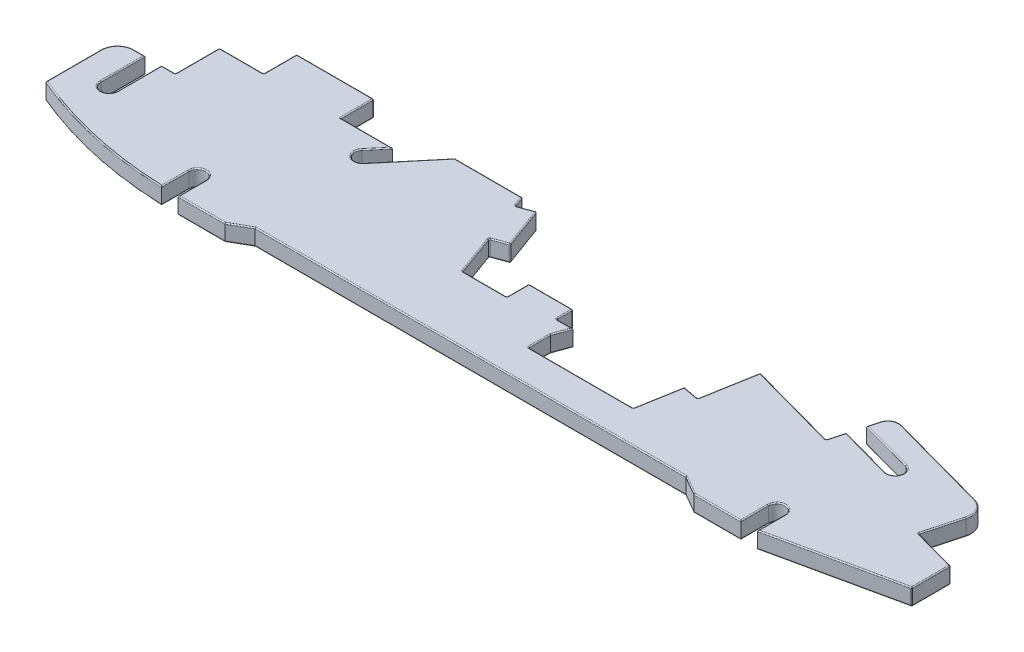
SolidWorks part; units mm, degrees
ref_plane "Front Plane" through (0, 0, 0) normal (0, 0, 1) x (1, 0, 0)
ref_plane "Top Plane" through (0, 0, 0) normal (0, 1, 0) x (1, 0, 0)
ref_plane "Right Plane" through (0, 0, 0) normal (1, 0, 0) x (0, 0, -1)
sketch "Sketch1" plane through (0, 0, 0) normal (0, 1, 0) x (1, 0, 0)
  line L0 (-1.5, 0) -> (-1.5, -5)
  line L1 (1.5, 0) -> (1.5, -5)
  line L2 (-103.5, -5) -> (-95, -5)
  line L3 (24.5, 0) -> (24.5, 7)
  line L4 (-103.5, -5) -> (-103.5, 0)
  line L5 (-106.5, 0) -> (-106.5, -5)
  line L6 (-128.5, 6) -> (-128.5, 14)
  line L7 (-125.5, 6) -> (-125.5, 14)
  line L8 (-133.5, 11) -> (-133.5, 1)
  line L9 (1.5, -5) -> (24.5, 0)
  line L10 (-91.5359, -3) -> (-13.4641, -3)
  line L11 (-95, -5) -> (-91.5359, -3)
  line L12 (-10, -5) -> (-13.4641, -3)
  line L13 (-10, -5) -> (-1.5, -5)
  line L14 (-105, 0) -> (0, 0) construction
  line L15 (-52.5, 0) -> (-52.5, -7.0386) construction
  line L16 (-48, 3) -> (-29, 3)
  line L18 (-48, 3) -> (-48, 7)
  line L19 (-48, 7) -> (-46.9081, 10)
  line L20 (-46.9081, 10) -> (-49.9081, 10)
  line L21 (-49.9081, 10) -> (-49.9081, 13)
  line L22 (-49.9081, 13) -> (-57.9081, 13)
  line L23 (-57.9081, 13) -> (-57.9081, 9)
  line L24 (-57.9081, 9) -> (-65.9081, 9)
  line L25 (-65.9081, 9) -> (-68.6443, 16.5175)
  line L26 (-84.3291, 26) -> (-72.0956, 26)
  line L27 (-68.6443, 16.5175) -> (-65.8252, 17.5436)
  line L28 (-65.8252, 17.5436) -> (-68.5613, 25.0611)
  line L29 (-68.5613, 25.0611) -> (-71.3804, 24.0351)
  line L30 (-71.3804, 24.0351) -> (-72.0956, 26)
  line L31 (-115, 28) -> (-101, 28)
  line L32 (-101, 28) -> (-101, 22)
  line L33 (-101, 22) -> (-91.6017, 22)
  line L34 (-91.6017, 22) -> (-94.1491, 18.9642)
  line L35 (-91.8509, 17.0358) -> (-84.3291, 26)
  line L36 (-115, 28) -> (-115, 22)
  line L37 (-115, 22) -> (-123, 22)
  line L38 (-123, 22) -> (-123, 14)
  line L39 (-123, 14) -> (-125.5, 14)
  line L41 (-29, 3) -> (-27.6108, 10.8785)
  line L42 (-27.6108, 10.8785) -> (-24.6564, 10.3575)
  line L43 (-24.6564, 10.3575) -> (-22.9562, 20)
  line L44 (24.5, 7) -> (16.587, 9.1677)
  line L45 (-6.5602, 15.5085) -> (-5.7676, 18.4019)
  line L46 (-5.7676, 18.4019) -> (3.8771, 15.7599)
  line L47 (4.6697, 18.6533) -> (-4.975, 21.2953)
  line L48 (-4.975, 21.2953) -> (-4.4466, 23.2243)
  line L49 (-1.9893, 24.6248) -> (16.3356, 19.6049)
  line L50 (18.4364, 15.9189) -> (16.587, 9.1677)
  line L51 (-6.5602, 15.5085) -> (-22.9562, 20)
  line L52 (-128.5, 14) -> (-130.5, 14)
  arc A0 (1.5, 0) -> (-1.5, 0) centre (0, 0) ccw
  arc A1 (-103.5, 0) -> (-106.5, 0) centre (-105, 0) ccw
  arc A2 (-128.5, 6) -> (-125.5, 6) centre (-127, 6) ccw
  arc A3 (-133.5, 11) -> (-130.5, 14) centre (-130.5, 11) cw
  arc A4 (-133.5, 1) -> (-106.5, -5) centre (-104.0092, 69.9586) ccw
  arc A5 (-94.1491, 18.9642) -> (-91.8509, 17.0358) centre (-93, 18) ccw
  arc A6 (3.8771, 15.7599) -> (4.6697, 18.6533) centre (4.2734, 17.2066) ccw
  arc A7 (16.3356, 19.6049) -> (18.4364, 15.9189) centre (15.543, 16.7115) cw
  arc A8 (-4.4466, 23.2243) -> (-1.9893, 24.6248) centre (-2.5177, 22.6959) cw
  point P68 (19.229, 18.8123)
  point P71 (-3.9182, 25.1532)
  dimension "D1" = 3
  dimension "D3" = 3
  dimension "D10" = 75
  dimension "D36" = 14
  dimension "D42" = 1.5
  dimension "D49" = 23
  dimension "D52" = 1.5
  dimension "D56" = 3
  dimension "D57" = 2
  dimension "D8" = 3
  dimension "D47" = 3
  dimension "D2" = 24.5
  dimension "D4" = 105
  dimension "D6" = 28.5
  dimension "D7" = 10.5
  dimension "D9" = 6
  dimension "D11" = 5
  dimension "D12" = 5
  dimension "D13" = 12
  dimension "D14" = 2
  dimension "D15" = 30
  dimension "D16" = 30
  dimension "D17" = 85
  dimension "D18" = 42.5
  dimension "D19" = 6
  dimension "D20" = 4
  dimension "D21" = 48
  dimension "D22" = 80
  dimension "D23" = 20
  dimension "D24" = 13
  dimension "D25" = 8
  dimension "D26" = 8
  dimension "D27" = 12
  dimension "D28" = 3
  dimension "D29" = 3
  dimension "D30" = 29
  dimension "D31" = 70
  dimension "D32" = 8
  dimension "D33" = 8
  dimension "D34" = 3
  dimension "D35" = 33
  dimension "D37" = 6
  dimension "D38" = 8
  dimension "D39" = 6.5
  dimension "D40" = 8
  dimension "D41" = 12
  dimension "D43" = 40
  dimension "D44" = 23
  dimension "D45" = 3
  dimension "D46" = 8
  dimension "D48" = 29
  dimension "D50" = 17
  dimension "D51" = 3
  dimension "D53" = 10
  dimension "D54" = 4
  dimension "D55" = 24
  dimension "D58" = 8
extrude "Boss-Extrude1" add sketch "Sketch1" along normal blind 3
fillet "Fillet1" radius 0.2 117 edges at (24.5, 1.5, -7) (-49.9081, 1.5, -13) (-57.9081, 1.5, -13) (-68.5613, 1.5, -25.0611) (1.5, 0, 2.5) (24.5, 0, -3.5) (20.5435, 0, -8.0838) (18.1494, 0, -18.197) (7.1732, 0, -22.1149) (-3.508, 0, -24.4335) (-4.7108, 0, -22.2598) (-0.1527, 0, -19.9743) (5.7201, 0, -16.8103) (-0.9453, 0, -17.0809) (-6.1639, 0, -16.9552) (-14.7582, 0, -17.7543) (-23.8063, 0, -15.1788) (-26.1336, 0, -10.618) (-28.3054, 0, -6.9392) (-38.5, 0, -3) (-47.454, 0, -8.5) (-48.4081, 0, -10) (-49.9081, 0, -11.5) (-53.9081, 0, -13) (-57.9081, 0, -11) (-61.9081, 0, -9) (-67.2762, 0, -12.7588) (-67.2347, 0, -17.0306) (-69.9709, 0, -24.5481) (-78.2123, 0, -26) (-88.09, 0, -21.5179) (-93.9642, 0, -16.8509) (-92.8754, 0, -20.4821) (-96.3009, 0, -22) (-108, 0, -28) (-115, 0, -25) (-119, 0, -22) (-123, 0, -18) (-124.25, 0, -14) (-125.5, 0, -10) (-127, 0, -4.5) (-128.5, 0, -10) (-129.5, 0, -14) (-133.5, 0, -6) (-120.279, 0, 3.2554) (-106.5, 0, 2.5) (-105, 0, -1.5) (-103.5, 0, 2.5) (-99.25, 0, 5) (-93.2679, 0, 4) (-52.5, 0, 3) (-11.7321, 0, 4) (-5.75, 0, 5) (-1.5, 0, 2.5) (0, 0, -1.5) (-1.5, 3, 2.5) (-5.75, 3, 5) (-11.7321, 3, 4) (-52.5, 3, 3) (-93.2679, 3, 4) (-99.25, 3, 5) (-103.5, 3, 2.5) (-105, 3, -1.5) (-106.5, 3, 2.5) (-133.5, 3, -6) (-129.5, 3, -14) (-128.5, 3, -10) (-127, 3, -4.5) (-124.25, 3, -14) (-123, 3, -18) (-119, 3, -22) (-115, 3, -25) (-108, 3, -28) (-101, 3, -25) (-96.3009, 3, -22) (-93.9642, 3, -16.8509) (-88.09, 3, -21.5179) (-71.738, 3, -25.0175) (-69.9709, 3, -24.5481) (-67.2347, 3, -17.0306) (-67.2762, 3, -12.7588) (-61.9081, 3, -9) (-57.9081, 3, -11) (-53.9081, 3, -13) (-49.9081, 3, -11.5) (-48.4081, 3, -10) (-47.454, 3, -8.5) (-38.5, 3, -3) (-28.3054, 3, -6.9392) (-26.1336, 3, -10.618) (-14.7582, 3, -17.7543) (-6.1639, 3, -16.9552) (-0.9453, 3, -17.0809) (5.7201, 3, -16.8103) (-0.1527, 3, -19.9743) (-4.7108, 3, -22.2598) (-3.508, 3, -24.4335) (7.1732, 3, -22.1149) (18.1494, 3, -18.197) (20.5435, 3, -8.0838) (13, 3, 2.5) (1.5, 3, 2.5) (0, 3, -1.5) (-115, 1.5, -22) (-115, 1.5, -28) (-133.5, 1.5, -1) (-123, 1.5, -14) (-6.5602, 1.5, -15.5085) (-24.6564, 1.5, -10.3575) (-27.6108, 1.5, -10.8785) (-57.9081, 1.5, -9) (-49.9081, 1.5, -10) (-101, 1.5, -28) (-68.6443, 1.5, -16.5175) (-71.3804, 1.5, -24.0351) (-132.6213, 0, -13.1213) (-132.6213, 3, -13.1213)
